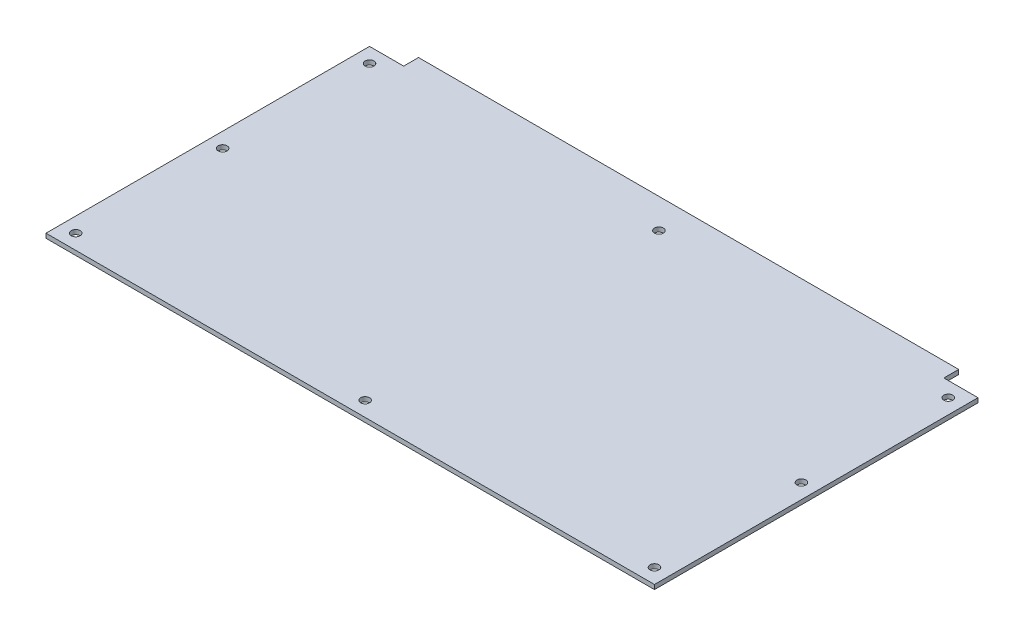
SolidWorks part; units mm, degrees
ref_plane "Alzado" through (0, 0, 0) normal (0, 0, 1) x (1, 0, 0)
ref_plane "Planta" through (0, 0, 0) normal (0, 1, 0) x (1, 0, 0)
ref_plane "Vista lateral" through (0, 0, 0) normal (1, 0, 0) x (0, 0, -1)
sketch "Croquis1" plane through (0, 0, 0) normal (0, 1, 0) x (1, 0, 0)
  line L0 (-182, 109) -> (-182, 119)
  line L1 (-205, 109) -> (-182, 109)
  line L2 (-205, 109) -> (-205, -109)
  line L3 (-205, -109) -> (205, -109)
  line L4 (205, 109) -> (205, -109)
  line L5 (-205, 109) -> (205, -109) construction
  line L6 (-205, -109) -> (205, 109) construction
  line L7 (0, 0) -> (0, 64.2611) construction
  line L8 (-182, 119) -> (182, 119)
  line L9 (182, 109) -> (182, 119)
  line L10 (205, 109) -> (182, 109)
  line L11 (0, 0) -> (-144.4747, 0) construction
  circle A0 centre (-195, -99) radius 3
  circle A1 centre (0, -99) radius 3
  circle A2 centre (-195, 0) radius 3
  circle A3 centre (-195, 99) radius 3
  circle A4 centre (195, 99) radius 3
  circle A5 centre (195, 0) radius 3
  circle A6 centre (195, -99) radius 3
  circle A7 centre (0, 99) radius 3
  point P0 (0, 0)
  point P15 (0, 119)
  dimension "D5" = 6
  dimension "D8" = 6
  dimension "D9" = 6
  dimension "D1" = 218
  dimension "D2" = 410
  dimension "D3" = 23
  dimension "D4" = 10
  dimension "D6" = 10
  dimension "D7" = 10
extrude "Saliente-Extruir1" add sketch "Croquis1" along normal blind 3
